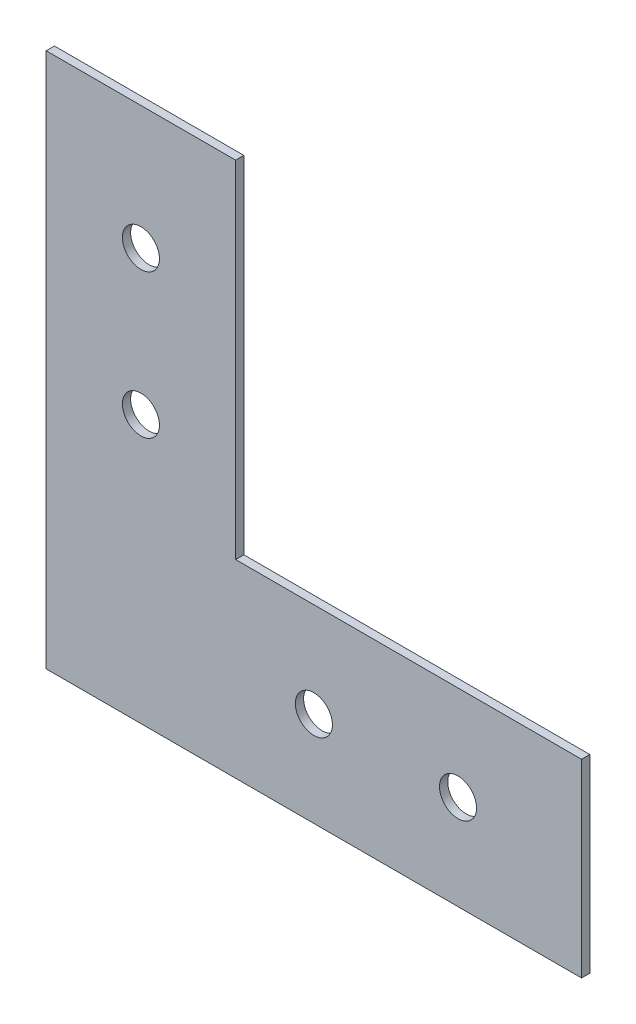
SolidWorks part; units mm, degrees
ref_plane "前视基准面" through (0, 0, 0) normal (0, 0, 1) x (1, 0, 0)
ref_plane "上视基准面" through (0, 0, 0) normal (0, 1, 0) x (1, 0, 0)
ref_plane "右视基准面" through (0, 0, 0) normal (1, 0, 0) x (0, 0, -1)
sketch "草图1" plane through (0, 0, 0) normal (0, 0, 1) x (1, 0, 0)
  line B0 (0, 130) -> (0, 0)
  line B1 (0, 0) -> (130, 0)
  line B2 (46, 130) -> (46, 46)
  line B3 (46, 46) -> (130, 46)
  line B4 (130, 46) -> (130, 0)
  line B5 (46, 130) -> (0, 130)
  circle B6 centre (23, 100) radius 4.5
  circle B7 centre (23, 65) radius 4.5
  circle B8 centre (65, 23) radius 4.5
  circle B9 centre (100, 23) radius 4.5
sketch_block_instance "A$C458E19C0-1"
sketch_block "A$C458E19C0"
extrude "凸台-拉伸1" add sketch "草图1" along normal blind 2
